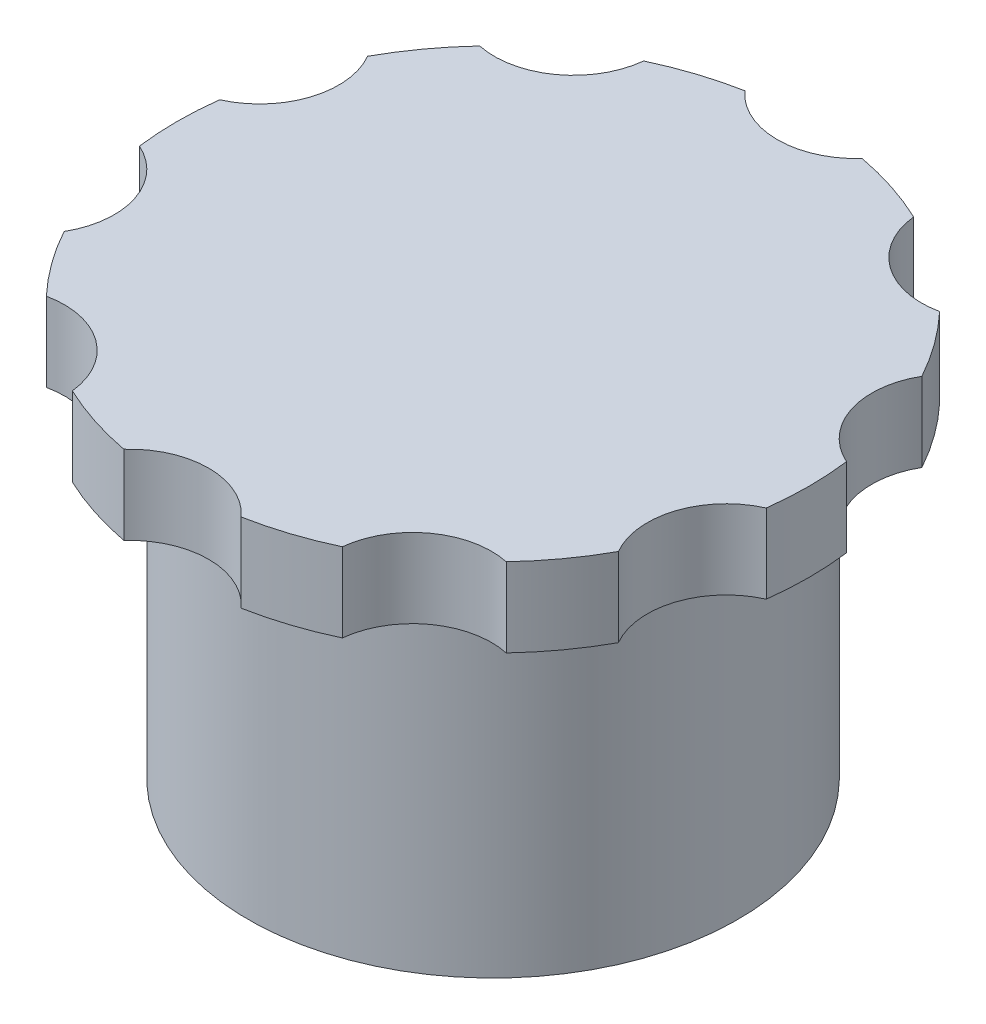
SolidWorks part; units mm, degrees
ref_plane "Alzado" through (0, 0, 0) normal (0, 0, 1) x (1, 0, 0)
ref_plane "Planta" through (0, 0, 0) normal (0, 1, 0) x (1, 0, 0)
ref_plane "Vista lateral" through (0, 0, 0) normal (1, 0, 0) x (0, 0, -1)
sketch "Croquis1" plane through (0, 0, 0) normal (0, 1, 0) x (1, 0, 0)
  circle A0 centre (0, 0) radius 10
  circle A1 centre (0, 0) radius 15.5
  dimension "D1" = 20
  dimension "D2" = 5.5
extrude "Saliente-Extruir1" add sketch "Croquis1" along normal blind 21
sketch "Croquis2" plane through (0, 21, 0) normal (0, 1, 0) x (1, 0, 0)
  circle A0 centre (0, 0) radius 23
  circle A1 centre (0, 0) radius 15.5 construction
  dimension "D1" = 7.5
extrude "Saliente-Extruir2" add sketch "Croquis2" along normal blind 5
sketch "Croquis3" plane through (0, 26, 0) normal (0, 1, 0) x (1, 0, 0)
  line L0 (0, 0) -> (0, 23) construction
  circle A0 centre (0, 23) radius 5
  circle A1 centre (0, 0) radius 23 construction
  circle A2 centre (13.5191, 18.6074) radius 5
  circle A3 centre (21.8743, 7.1074) radius 5
  circle A4 centre (21.8743, -7.1074) radius 5
  circle A5 centre (13.5191, -18.6074) radius 5
  circle A6 centre (0, -23) radius 5
  circle A7 centre (-13.5191, -18.6074) radius 5
  circle A8 centre (-21.8743, -7.1074) radius 5
  circle A9 centre (-21.8743, 7.1074) radius 5
  circle A10 centre (-13.5191, 18.6074) radius 5
  point P39 (0, 0)
  dimension "D1" = 10
  dimension "D2" = 10
extrude "Cortar-Extruir1" cut sketch "Croquis3" against normal blind 5
sketch "Croquis4" plane through (0, 26, 0) normal (0, 1, 0) x (1, 0, 0)
  circle A0 centre (0, 0) radius 20
  circle A1 centre (0, 0) radius 23
  dimension "D1" = 40
extrude "Cortar-Extruir2" cut sketch "Croquis4" against normal blind 5
